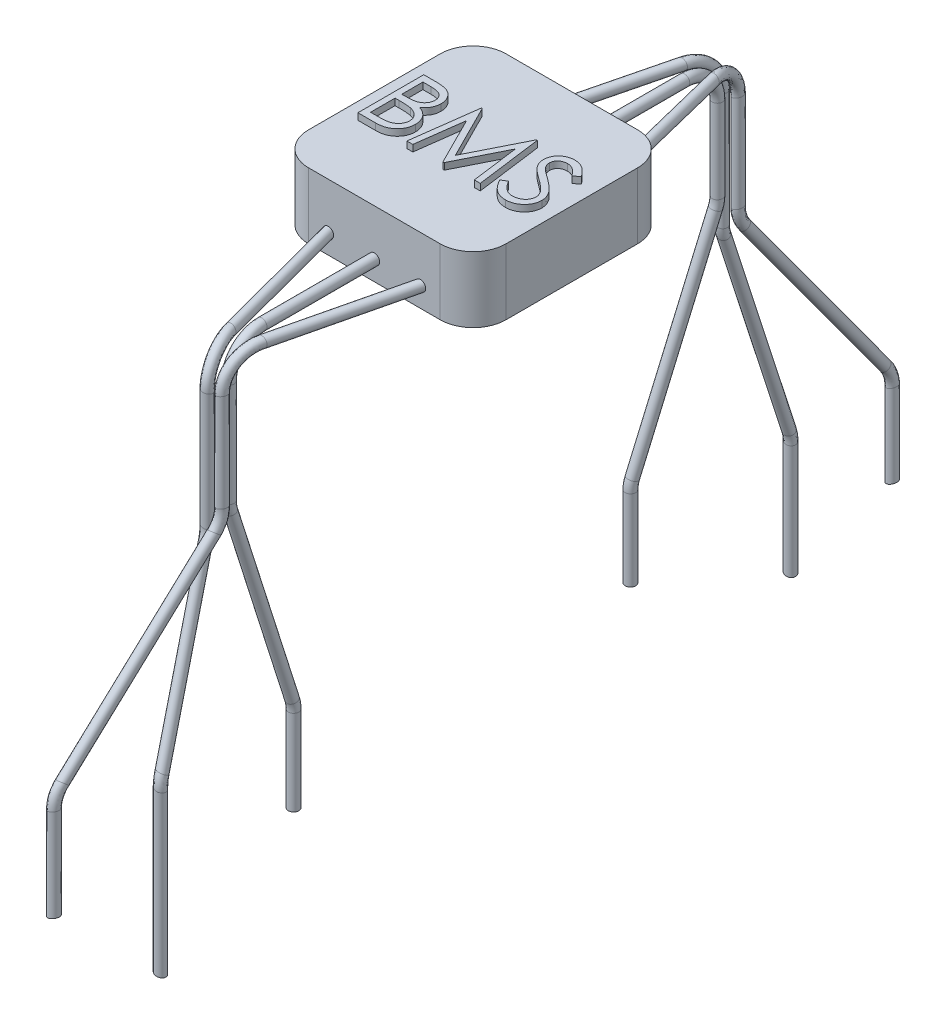
SolidWorks part; units mm, degrees
ref_plane "Front Plane" through (0, 0, 0) normal (0, 0, 1) x (1, 0, 0)
ref_plane "Top Plane" through (0, 0, 0) normal (0, 1, 0) x (1, 0, 0)
ref_plane "Right Plane" through (0, 0, 0) normal (1, 0, 0) x (0, 0, -1)
sketch "Sketch1" plane through (0, 0, 0) normal (0, 1, 0) x (1, 0, 0)
  line L1 (-10, -15) -> (10, -15)
  line L2 (-15, -10) -> (-15, 10)
  line L3 (-10, 15) -> (10, 15)
  line L4 (15, -10) -> (15, 10)
  line L5 (-15, -15) -> (15, 15) construction
  line L6 (-15, 15) -> (15, -15) construction
  arc A0 (15, -10) -> (10, -15) centre (10, -10) cw
  arc A1 (-10, -15) -> (-15, -10) centre (-10, -10) cw
  arc A2 (10, 15) -> (15, 10) centre (10, 10) cw
  arc A3 (-10, 15) -> (-15, 10) centre (-10, 10) ccw
  point P0 (0, 0)
  dimension "D3" = 5
  dimension "D1" = 30
  dimension "D2" = 30
extrude "Boss-Extrude1" add sketch "Sketch1" along normal blind 10
sketch "Sketch2" plane through (0, 10, 0) normal (0, 1, 0) x (1, 0, 0)
  line L3 (-15, -5) -> (15, -5) construction
  line L4 (-15, 5) -> (15, 5) construction
  text T0 "BMS" font "Century Gothic" height 10
extrude "Boss-Extrude2" add sketch "Sketch2" along normal blind 1
sketch "Sketch3" plane through (0, 0, 15) normal (0, 0, 1) x (1, 0, 0)
  circle A2 centre (7, 3) radius 0.8
  dimension "D3" = 1.6
sketch3d "3DSketch1"
  line L0 (6.967, 3.0055, 14.8222) -> (2.2661, 3.0055, 34.437)
  line L1 (1.1009, -1.9945, 39.2993) -> (1.1009, -16.7953, 39.2993)
  line L2 (0.8926, -19.8601, 40.3279) -> (-2.9925, -45.1033, 59.5229)
  line L3 (-3.2007, -48.1682, 60.5515) -> (-3.2007, -62.2, 60.5515)
  arc A0 (-2.9925, -45.1033, 59.5229) -> (-3.2007, -48.1682, 60.5515) centre (-2.2088, -48.1682, 55.6509) ccw
  arc A1 (1.1009, -16.7953, 39.2993) -> (0.8926, -19.8601, 40.3279) centre (0.1089, -16.7953, 44.1999) ccw
  arc A2 (2.2661, 3.0055, 34.437) -> (1.1009, -1.9945, 39.2993) centre (2.2661, -1.9945, 34.437) ccw
  circle A4 centre (-3.2007, -62.2, 60.5515) radius 0.25 construction
  point P9 (-3.2007, -46.4561, 60.5515)
  point P10 (2.6918, -48.1682, 56.6428)
  point P13 (1.1009, -18.5074, 39.2993)
  point P14 (-4.7917, -16.7953, 43.208)
  point P17 (1.1009, 3.0055, 39.2993)
  point P18 (7.1285, -1.9945, 35.6023)
  point P24 (-3.2007, -62.2, 60.5515)
  point P28 (-3.2007, -61.95, 60.5515)
  dimension "D1" = 5
sweep "Sweep1" add profiles "Sketch3" path "3DSketch1"
sketch "Sketch7" plane through (0, 0, 15) normal (0, 0, 1) x (1, 0, 0)
  circle A0 centre (0, 3) radius 0.8
  dimension "D1" = 1.6
  dimension "D2" = 3
sketch3d "3DSketch2"
  line L0 (0, 3, 15) -> (0, 3, 32.107)
  line L1 (0, -2, 37.107) -> (0, -17.7106, 37.107)
  line L2 (0.0204, -19.1465, 36.8974) -> (0.8515, -47.7716, 28.3559)
  line L3 (0.8719, -49.2075, 28.1463) -> (0.8719, -62.2, 28.1463)
  circle A0 centre (0.8719, -62.2, 28.1463) radius 0.25 construction
  arc A1 (0.8515, -47.7716, 28.3559) -> (0.8719, -49.2075, 28.1463) centre (0.3877, -49.2075, 33.1228) ccw
  arc A2 (0, -17.7106, 37.107) -> (0.0204, -19.1465, 36.8974) centre (0.4842, -17.7106, 32.1305) ccw
  arc A3 (0, -2, 37.107) -> (0, 3, 32.107) centre (0, -2, 32.107) ccw
  point P7 (0.8719, -61.95, 28.1463)
  point P11 (0.8719, -48.4741, 28.1463)
  point P12 (-4.5888, -49.2075, 32.6386)
  point P15 (0, -18.444, 37.107)
  point P16 (5.4607, -17.7106, 32.6147)
  point P19 (0, 3, 37.107)
  point P20 (-5, -2, 32.107)
  dimension "D1" = 5
sweep "Sweep2" add profiles "Sketch7" path "3DSketch2"
sketch "Sketch8" plane through (0, 0, 15) normal (0, 0, 1) x (1, 0, 0)
  line L0 (-10, 0) -> (10, 0) construction
  circle A0 centre (-7, 3) radius 0.8
  circle A1 centre (0, 3) radius 0.8 construction
  dimension "D1" = 1.6
  dimension "D2" = 3
  dimension "D3" = 7
sketch3d "3DSketch3"
  line L0 (-7, 3, 15) -> (-2.3432, 2.3413, 34.4739)
  line L1 (-1.2186, -2.656, 39.1769) -> (-1.2186, -20.4992, 39.1769)
  line L2 (-1.1033, -22.4283, 39.5465) -> (1.8848, -46.4329, 49.1304)
  line L3 (2, -48.3621, 49.5) -> (2, -72.7, 49.5)
  line L4 (2, -79.2, 49.5) -> (2, -77.2, 49.5) construction
  arc A0 (-1.2186, -20.4992, 39.1769) -> (-1.1033, -22.4283, 39.5465) centre (0.2697, -20.4992, 43.9503) ccw
  arc A1 (-1.2186, -2.656, 39.1769) -> (-2.3432, 2.3413, 34.4739) centre (-2.3814, -2.656, 34.314) ccw
  arc A2 (1.8848, -46.4329, 49.1304) -> (2, -48.3621, 49.5) centre (0.5117, -48.3621, 44.7266) ccw
  point P7 (-1.2186, -21.5026, 39.1769)
  point P8 (-4.5037, -20.4992, 45.4385)
  point P11 (-1.2186, 2.1822, 39.1769)
  point P12 (-7.2443, -2.656, 35.4769)
  point P15 (2, -47.3586, 49.5)
  point P16 (5.2851, -48.3621, 43.2384)
  point P17 (2, -72.7, 49.5)
  dimension "D1" = 5
sweep "Sweep4" add profiles "Sketch8" path "3DSketch3"
ref_plane "Plane1" through (0, 0, 0) normal (0, 0, 1) x (1, 0, 0)
sketch "Sketch9" plane through (0, 0, -15) normal (0, 0, -1) x (-1, 0, 0)
  line L0 (-10, 0) -> (10, 0) construction
  circle A0 centre (-7, 3) radius 0.8
  dimension "D3" = 1.6
  dimension "D1" = 3
  dimension "D2" = 7
sketch3d "3DSketch4"
  line L0 (7, 3, -15) -> (2.1778, 3, -34.429)
  line L1 (0.9734, -2, -39.2818) -> (0.9734, -16.6714, -39.2818)
  line L2 (1.0752, -19.5769, -40.2071) -> (3.1934, -46.6962, -59.455)
  line L3 (3.2952, -49.6017, -60.3802) -> (3.2952, -62.2, -60.3802)
  circle A0 centre (3.2952, -62.2, -60.3802) radius 0.25 construction
  arc A1 (3.1934, -46.6962, -59.455) -> (3.2952, -49.6017, -60.3802) centre (2.7483, -49.6017, -55.4102) ccw
  arc A2 (1.0752, -19.5769, -40.2071) -> (0.9734, -16.6714, -39.2818) centre (1.5203, -16.6714, -44.2518) ccw
  arc A3 (0.9734, -2, -39.2818) -> (2.1778, 3, -34.429) centre (2.1778, -2, -34.429) ccw
  point P7 (3.2952, -61.95, -60.3802)
  point P11 (3.2952, -47.9998, -60.3802)
  point P12 (-2.2217, -49.6017, -55.9572)
  point P15 (0.9734, -18.2733, -39.2818)
  point P16 (-3.4497, -16.6714, -44.7987)
  point P19 (0.9734, 3, -39.2818)
  point P20 (7.0306, -2, -35.6335)
  dimension "D1" = 5
sweep "Sweep5" add profiles "Sketch9" path "3DSketch4"
sketch "Sketch10" plane through (0, 0, -15) normal (0, 0, -1) x (-1, 0, 0)
  circle A0 centre (0, 3) radius 0.8
  dimension "D2" = 1.6
  dimension "D1" = 3
sketch3d "3DSketch5"
  line L0 (0, 3, -15) -> (0, 3, -32.1201)
  line L1 (0, -2, -37.1201) -> (0, -14.7123, -37.1201)
  line L2 (-0.0679, -16.2075, -36.9016) -> (-3.0645, -48.4376, -27.2566)
  line L3 (-3.1324, -49.9327, -27.0381) -> (-3.1324, -62.2, -27.0381)
  circle A0 centre (-3.1324, -62.2, -27.0381) radius 0.25 construction
  arc A1 (-3.0645, -48.4376, -27.2566) -> (-3.1324, -49.9327, -27.0381) centre (-1.6489, -49.9327, -31.813) ccw
  arc A2 (0, -14.7123, -37.1201) -> (-0.0679, -16.2075, -36.9016) centre (-1.4835, -14.7123, -32.3452) ccw
  arc A3 (0, -2, -37.1201) -> (0, 3, -32.1201) centre (0, -2, -32.1201) ccw
  point P7 (-3.1324, -61.95, -27.0381)
  point P12 (-3.1324, -49.1677, -27.0381)
  point P13 (3.126, -49.9327, -30.3295)
  point P16 (0, -15.4774, -37.1201)
  point P17 (-6.2584, -14.7123, -33.8287)
  point P20 (0, 3, -37.1201)
  point P21 (5, -2, -32.1201)
  dimension "D1" = 5
sweep "Sweep6" add profiles "Sketch10" path "3DSketch5"
sketch "Sketch11" plane through (0, 0, -15) normal (0, 0, -1) x (-1, 0, 0)
  line L0 (-10, 0) -> (10, 0) construction
  circle A0 centre (7, 3) radius 0.8
  circle A1 centre (0, 3) radius 0.8 construction
  dimension "D1" = 1.6
  dimension "D2" = 7
  dimension "D3" = 3
sketch3d "3DSketch6"
  line L0 (-7, 3, -15) -> (-2.2709, 3, -34.0325)
  line L1 (-1.0652, -2, -38.8849) -> (-1.0652, -19.7822, -38.8849)
  line L2 (-1.0652, -21.3207, -39.1275) -> (-1.0652, -52.0145, -49.0535)
  line L3 (-1.0652, -53.5529, -49.2961) -> (-1.0652, -70.881, -49.2961)
  arc A0 (-1.0652, -53.5529, -49.2961) -> (-1.0652, -52.0145, -49.0535) centre (-1.0652, -53.5529, -44.2961) ccw
  arc A1 (-1.0652, -21.3207, -39.1275) -> (-1.0652, -19.7822, -38.8849) centre (-1.0652, -19.7822, -43.8849) ccw
  arc A2 (-1.0652, -2, -38.8849) -> (-2.2709, 3, -34.0325) centre (-2.2709, -2, -34.0325) ccw
  point P7 (-1.0652, -52.7646, -49.2961)
  point P8 (3.9348, -53.5529, -44.2961)
  point P11 (-1.0652, -20.5706, -38.8849)
  point P12 (-6.0652, -19.7822, -43.8849)
  point P15 (-1.0652, 3, -38.8849)
  point P16 (2.5815, -2, -32.8268)
  dimension "D1" = 5
sweep "Sweep7" add profiles "Sketch11" path "3DSketch6"
